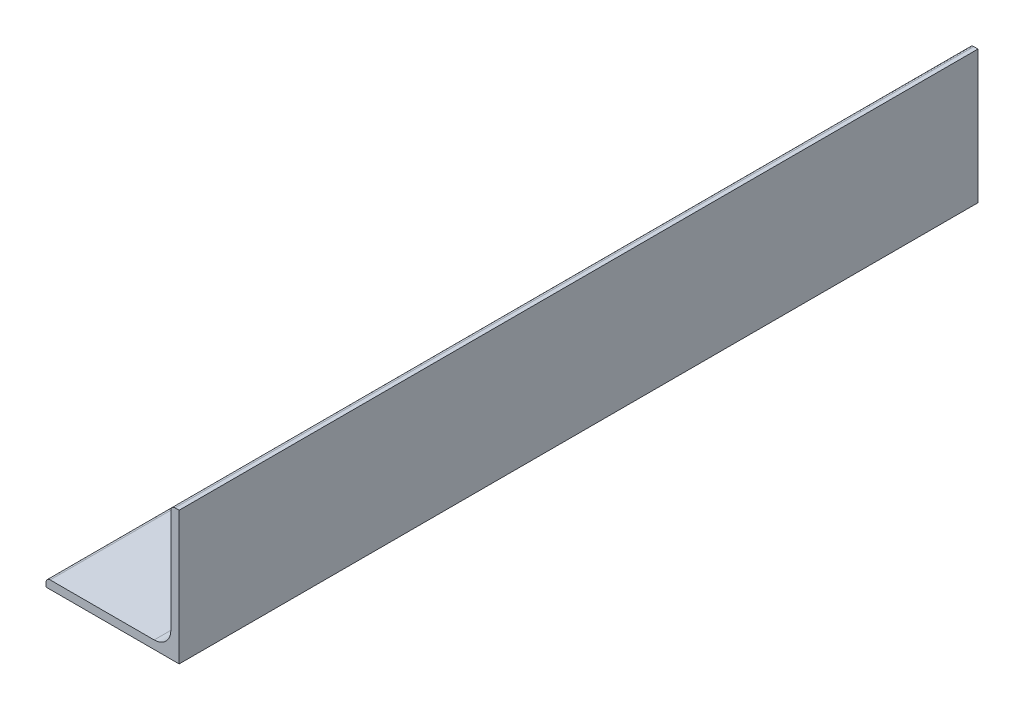
SolidWorks part; units mm, degrees
ref_plane "Front Plane" through (0, 0, 0) normal (0, 0, 1) x (1, 0, 0)
ref_plane "Top Plane" through (0, 0, 0) normal (0, 1, 0) x (1, 0, 0)
ref_plane "Right Plane" through (0, 0, 0) normal (1, 0, 0) x (0, 0, -1)
sketch "Sketch0" plane through (0, 0, 0) normal (0, 0, 1) x (1, 0, 0)
  line L0 (-25.4, -25.4) -> (25.4, -25.4)
  line L1 (25.4, -25.4) -> (25.4, 25.4)
  line L2 (25.4, 0) -> (0, 0) construction
  line L3 (0, 0) -> (0, -25.4) construction
  line L4 (22.225, -15.875) -> (22.225, 25.4) construction
  line L5 (15.875, -22.225) -> (-25.4, -22.225) construction
  arc A0 (22.225, -15.875) -> (15.875, -22.225) centre (15.875, -15.875) cw
  point P3 (20.3651, -20.3651)
  dimension "Inside Corner Radius" = 6.35
  dimension "Outside Height" = 50.8
  dimension "Inside Height" = 47.625
  dimension "Inside Width" = 47.625
  dimension "Wall Thickness" = 3.175
  dimension "D1" = 3.175
  dimension "Outside Width" = 50.8
sketch "Sketch1" plane through (0, 0, 0) normal (1, 0, 0) x (0, 0, -1)
  line L0 (152.4, 0) -> (-152.4, 0)
  point P4 (0, 0)
  dimension "Length" = 304.8
sketch "Sketch2" plane through (0, 0, 0) normal (0, 0, 1) x (1, 0, 0)
  line L0 (-25.4, -25.4) -> (25.4, -25.4)
  line L1 (25.4, -25.4) -> (25.4, 25.4)
  line L2 (25.4, 25.4) -> (22.225, 25.4) construction
  line L3 (22.225, 23.8125) -> (22.225, -15.875)
  line L4 (15.875, -22.225) -> (-23.8125, -22.225)
  line L5 (-25.4, -25.4) -> (-25.4, -22.225) construction
  line L6 (23.8125, 25.4) -> (25.4, 25.4)
  line L7 (-25.4, -23.8125) -> (-25.4, -25.4)
  line L8 (25.4, 0) -> (0, 0) construction
  line L9 (0, 0) -> (0, -25.4) construction
  arc A0 (22.225, 23.8125) -> (23.8125, 25.4) centre (23.8125, 23.8125) cw
  arc A1 (-25.4, -23.8125) -> (-23.8125, -22.225) centre (-23.8125, -23.8125) cw
  arc A2 (22.225, -15.875) -> (15.875, -22.225) centre (15.875, -15.875) cw
  dimension "Inside Radius" = 6.35
  dimension "Height" = 50.8
  dimension "Width" = 50.8
  dimension "Thickness" = 3.175
extrude "Boss-Extrude1" add sketch "Sketch2" along normal mid plane 304.8
sketch "Break Locations" plane through (0, 0, 0) normal (1, 0, 0) x (0, 0, -1)
  line L0 (-100.584, 0) -> (100.584, 0)
  line L1 (-152.4, -25.4) -> (-152.4, 25.4) construction
  line L2 (152.4, -25.4) -> (152.4, 25.4) construction
  point P0 (-109.22, 0)
  point P1 (109.22, 0)
  point P10 (0, 0)
  point P11 (100.584, 0)
  point P13 (-100.584, 0)
  dimension "D1" = 43.18
  dimension "D2" = 43.18
  dimension "D3" = 51.816
equation "\"D1@Break Locations\" = .85 * \"Height@Sketch2\""
equation "\"D2@Break Locations\"=\"D1@Break Locations\""
equation "\"Thickness@Sketch2\"=\"wall thickness@sketch0\""
equation "\"Height@Sketch2\"=\"outside height@sketch0\""
equation "\"Width@Sketch2\"=\"outside width@sketch0\""
equation "\"Inside Radius@Sketch2\"=\"inside corner radius@sketch0\""
equation "\"Length@Boss-Extrude1\"=\"length@sketch1\""
equation "\"D3@Break Locations\"=\"D2@Break Locations\"*1.2"
equation "\"D1@Sketch0\"=\"Wall Thickness@Sketch0\""
